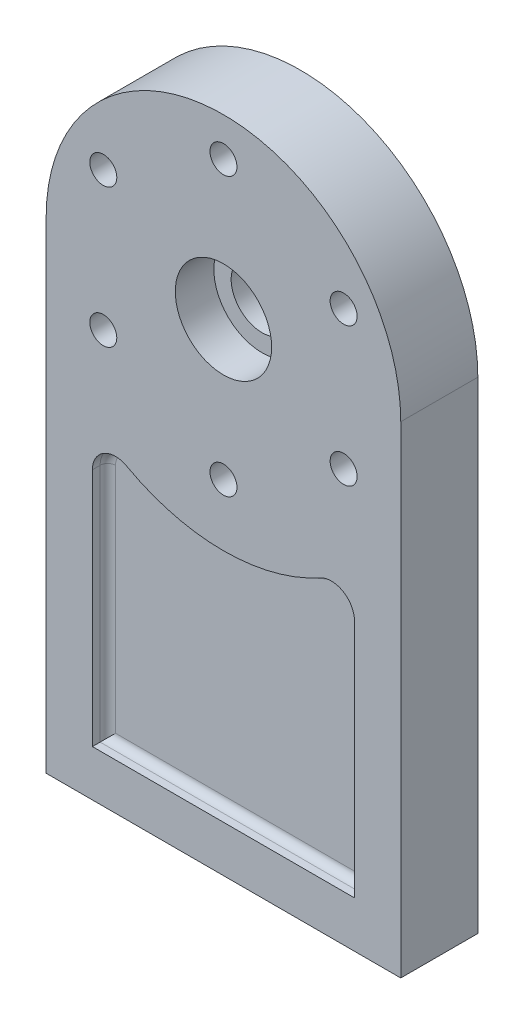
SolidWorks part; units mm, degrees
ref_plane "Front Plane" through (0, 0, 0) normal (0, 0, 1) x (1, 0, 0)
ref_plane "Top Plane" through (0, 0, 0) normal (0, 1, 0) x (1, 0, 0)
ref_plane "Right Plane" through (0, 0, 0) normal (1, 0, 0) x (0, 0, -1)
sketch "Sketch1" plane through (0, 0, 0) normal (0, 0, 1) x (1, 0, 0)
  line L7 (-46.3481, 124.9995) -> (-46.3481, 0)
  line L8 (-46.3481, 0) -> (45.6519, 0)
  line L9 (45.6519, 124.9995) -> (45.6519, 0)
  arc A0 (45.6519, 124.9995) -> (-46.3481, 124.9995) centre (-0.3481, 124.9995) ccw
  circle A1 centre (-0.3481, 124.9995) radius 8
  point P4 (0, 0)
  dimension "D1" = 92
  dimension "D3" = 16
  dimension "D2" = 125
extrude "Boss-Extrude1" add sketch "Sketch1" along normal mid plane 20
sketch "Sketch2" plane through (0, 0, 10) normal (0, 0, 1) x (1, 0, 0)
  circle A0 centre (-0.3481, 124.9995) radius 12.5
  dimension "D1" = 25
extrude "Cut-Extrude1" cut sketch "Sketch2" against normal blind 10
sketch "Sketch3" plane through (0, 0, 10) normal (0, 0, 1) x (1, 0, 0)
  circle A0 centre (-0.3481, 124.9995) radius 36 construction
  circle A1 centre (-0.3481, 160.9995) radius 3.5
  dimension "D1" = 72
  dimension "D2" = 7
extrude "Cut-Extrude2" cut sketch "Sketch3" against normal blind 40 contours A1
sketch "Sketch4" plane through (0, 0, -10) normal (0, 0, -1) x (-1, 0, 0)
  circle A0 centre (0.3481, 160.9995) radius 6
  dimension "D1" = 12
extrude "Cut-Extrude3" cut sketch "Sketch4" against normal blind 6
pattern_circular "CirPattern1" count 6 over 360 about axis through (-0.3481, 124.9995, 0) along (0, 0, 1) of "Cut-Extrude2", "Cut-Extrude3"
hole_wizard "Tap Drill for M10x1.25 Tap1" positions "Sketch11" profile "Sketch13" hole size "M10x1.25" standard "ISO"
sketch "Sketch11" plane through (0, 0, 0) normal (0, -1, 0) x (-1, 0, 0)
  line L0 (46.3481, -10) -> (-45.6519, -10) construction
  line L1 (-45.6519, -10) -> (-45.6519, 10) construction
  point P0 (-29.6519, 0)
  point P2 (30.3481, 0)
  dimension "D1" = 60
  dimension "D2" = 10
  dimension "D3" = 16
sketch "Sketch13" plane through (29.6519, 0, 0) normal (1, 0, 0) x (0, 0, -1)
  line L0 (0, 0) -> (0, 26.6438)
  line L1 (0, 26.6438) -> (4.4, 24)
  line L2 (4.4, 24) -> (4.4, 0.025)
  line L3 (4.4, 0.025) -> (4.425, 0)
  line L5 (4.425, 0) -> (0, 0)
  line L6 (-4.4, 0.025) -> (-4.425, 0) construction
  line L10 (0, 26.6438) -> (-4.4, 24) construction
  line L11 (0, -6.35) -> (0, 107.95) construction
  dimension "Hole Dia." = 8.8
  dimension "Hole Depth" = 24
  dimension "Near C'Sink Dia." = 8.85
  dimension "Near C'Sink Angle" = 90
  dimension "Drill Angle" = 118
sketch "Sketch15" plane through (0, 0, 10) normal (0, 0, 1) x (1, 0, 0)
  line L6 (33.6519, 12) -> (33.6519, 124.9995)
  line L7 (-34.3481, 12) -> (33.6519, 12)
  line L8 (-34.3481, 124.9995) -> (-34.3481, 12)
  line L9 (33.6519, 12) -> (33.6519, 74.2058)
  line L10 (-34.3481, 12) -> (33.6519, 12)
  line L11 (-34.3481, 74.2058) -> (-34.3481, 12)
  arc A0 (-25.4516, 79.4603) -> (24.7553, 79.4603) centre (-0.3481, 124.9995) ccw
  arc A1 (24.7553, 79.4603) -> (33.6519, 74.2058) centre (27.6519, 74.2058) cw
  arc A2 (-25.4516, 79.4603) -> (-34.3481, 74.2058) centre (-28.3481, 74.2058) ccw
  dimension "D1" = 104
  dimension "D3" = 6
  dimension "D2" = 12
extrude "Cut-Extrude4" cut sketch "Sketch15" against normal blind 4
fillet "Fillet2" radius 2 6 edges at (33.6519, 43.1029, 6) (-0.3481, 12, 6) (-34.3481, 43.1029, 6) (-31.3994, 79.372, 6) (-0.3481, 72.9995, 6) (30.7032, 79.372, 6)
mirror "Mirror5" about plane through (0, 0, 0) normal (0, 0, 1) of "Cut-Extrude4", "Fillet2"
